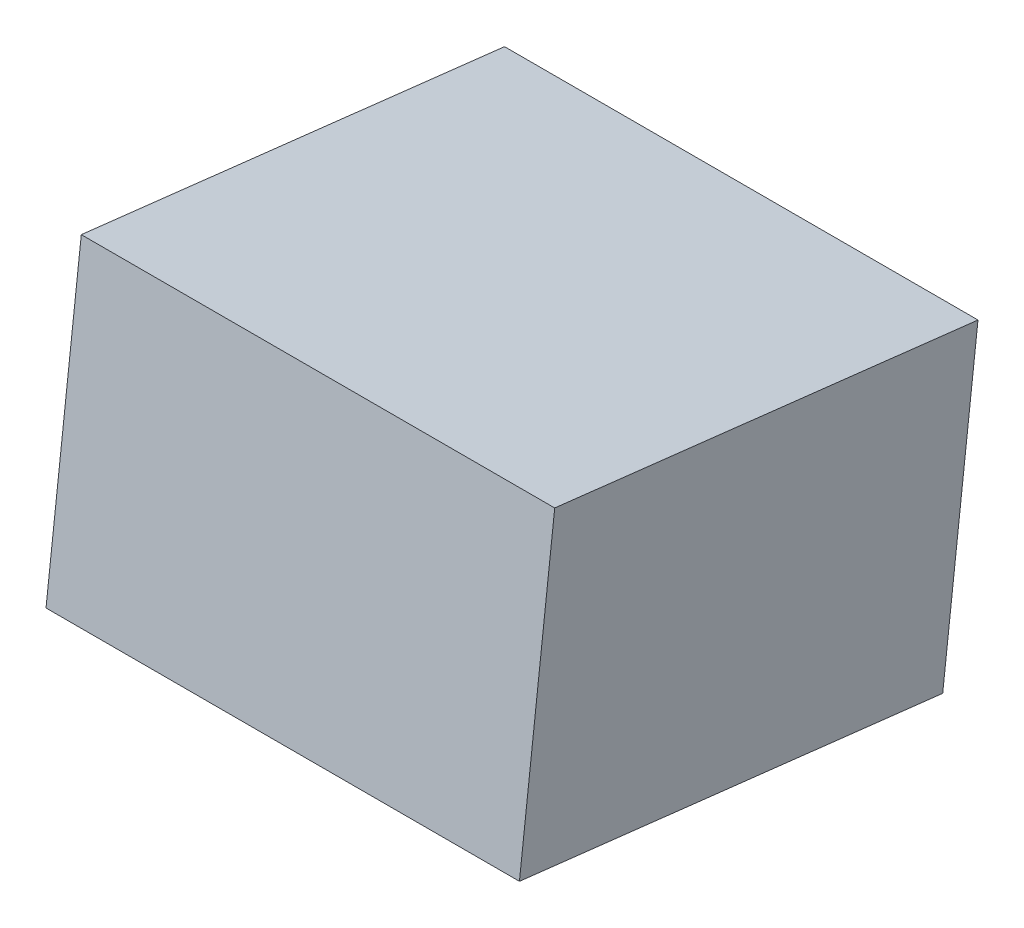
SolidWorks part; units mm, degrees
ref_plane "Front Plane" through (0, 0, 0) normal (0, 0, 1) x (1, 0, 0)
ref_plane "Top Plane" through (0, 0, 0) normal (0, 1, 0) x (1, 0, 0)
ref_plane "Right Plane" through (0, 0, 0) normal (1, 0, 0) x (0, 0, -1)
sketch "Sketch1" plane through (0, 358.8799, -41.4225) normal (0, 0.9934, -0.1147) x (1, 0, 0)
  line L1 (-231.6731, 103.1066) -> (-31.6731, 103.1066)
  line L2 (-231.6731, 103.1066) -> (-231.6731, 283.1066)
  line L3 (-231.6731, 283.1066) -> (-31.6731, 283.1066)
  line L4 (-31.6731, 103.1066) -> (-31.6731, 283.1066)
  line L5 (-231.6731, 103.1066) -> (-31.6731, 283.1066) construction
  line L6 (-231.6731, 283.1066) -> (-31.6731, 103.1066) construction
  point P0 (-131.6731, 193.1066)
  dimension "D1" = 180
  dimension "D2" = 200
extrude "Boss-Extrude1" add sketch "Sketch1" along normal blind 130
